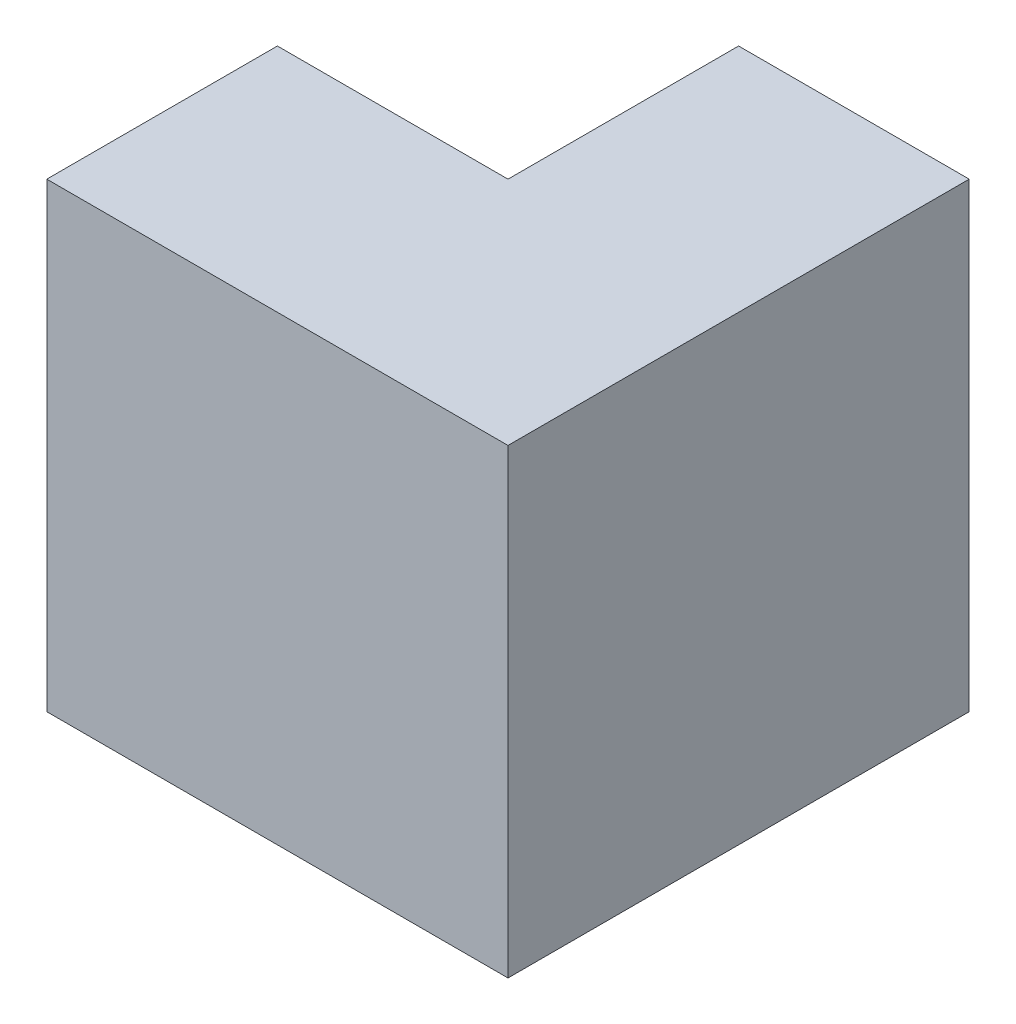
SolidWorks part; units mm, degrees
ref_plane "前视基准面" through (0, 0, 0) normal (0, 0, 1) x (1, 0, 0)
ref_plane "上视基准面" through (0, 0, 0) normal (0, 1, 0) x (1, 0, 0)
ref_plane "右视基准面" through (0, 0, 0) normal (1, 0, 0) x (0, 0, -1)
sketch "草图1" plane through (0, 0, 0) normal (0, 1, 0) x (1, 0, 0)
  line L1 (-6.7808, 7.1918) -> (13.2192, 7.1918)
  line L2 (-6.7808, 7.1918) -> (-6.7808, -12.8082)
  line L3 (-6.7808, -32.8082) -> (13.2192, -32.8082)
  line L4 (13.2192, 7.1918) -> (13.2192, -32.8082)
  line L5 (-6.7808, 7.1918) -> (13.2192, -32.8082) construction
  line L6 (-6.7808, -32.8082) -> (13.2192, 7.1918) construction
  line L7 (-6.7808, -32.8082) -> (-26.7808, -32.8082)
  line L9 (-6.7808, -12.8082) -> (-26.7808, -12.8082)
  line L10 (-26.7808, -32.8082) -> (-26.7808, -12.8082)
  line L11 (-6.7808, -32.8082) -> (-26.7808, -12.8082) construction
  line L12 (-6.7808, -12.8082) -> (-26.7808, -32.8082) construction
  point P4 (3.2192, -12.8082)
  point P8 (-16.7808, -22.8082)
  dimension "D1" = 20
  dimension "D2" = 40
  dimension "D3" = 20
  dimension "D4" = 20
extrude "凸台-拉伸1" add sketch "草图1" along normal blind 40
sketch "草图2" plane through (0, 0, 0) normal (0, -1, 0) x (1, 0, 0)
  line L0 (-6.7808, -7.1918) -> (-26.7808, 12.8082)
  line L1 (-26.7808, 12.8082) -> (-6.7808, 12.8082)
  line L2 (-6.7808, 12.8082) -> (-6.7808, -7.1918)
  point P6 (-6.7808, 12.8082)
extrude "凸台-拉伸2" add sketch "草图2" against normal blind 40
ref_plane "基准面1" through (0, 0, 12.8082) normal (0, 0, 1) x (1, 0, 0)
sketch "草图3" plane through (0, 0, 12.8082) normal (0, 0, 1) x (1, 0, 0)
  line L0 (-6.7808, 40) -> (-26.7808, 0)
  line L1 (-26.7808, 40) -> (13.2192, 40) construction
  line L2 (-26.7808, 40) -> (-26.7808, 0) construction
  line L3 (-26.7808, 40) -> (-26.7808, 0) construction
  line L4 (-26.7808, 0) -> (-26.7808, 40)
  line L5 (-26.7808, 40) -> (-6.7808, 40)
extrude "切除-拉伸1" cut sketch "草图3" against normal blind 40
ref_plane "基准面2" through (-6.7808, 0, 0) normal (1, 0, 0) x (0, 0, -1)
sketch "草图4" plane through (-6.7808, 0, 0) normal (1, 0, 0) x (0, 0, -1)
  line L0 (-12.8082, 40) -> (7.1918, 0)
  line L1 (-32.8082, 40) -> (7.1918, 40) construction
  line L5 (-12.8082, 40) -> (7.1918, 40)
  line L6 (7.1918, 40) -> (7.1918, 0)
extrude "切除-拉伸2" cut sketch "草图4" against normal blind 40
